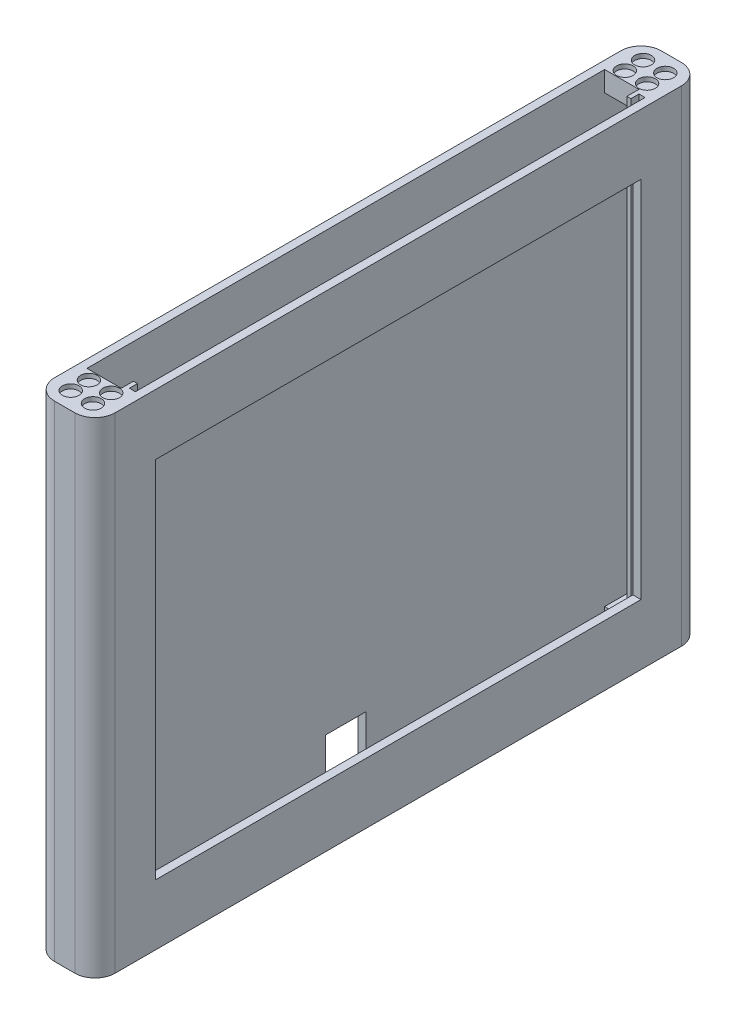
SolidWorks part; units mm, degrees
ref_plane "Front Plane" through (0, 0, 0) normal (0, 0, 1) x (1, 0, 0)
ref_plane "Top Plane" through (0, 0, 0) normal (0, 1, 0) x (1, 0, 0)
ref_plane "Right Plane" through (0, 0, 0) normal (1, 0, 0) x (0, 0, -1)
sketch "Sketch1" plane through (0, 0, 0) normal (1, 0, 0) x (0, 0, -1)
  line L1 (-75, -60) -> (75, -60)
  line L2 (-75, -60) -> (-75, 60)
  line L3 (-75, 60) -> (75, 60)
  line L4 (75, -60) -> (75, 60)
  line L5 (-75, -60) -> (75, 60) construction
  line L6 (-75, 60) -> (75, -60) construction
  point P0 (0, 0)
  dimension "D1" = 150
  dimension "D2" = 120
extrude "Boss-Extrude1" add sketch "Sketch1" against normal blind 15
shell "Shell1" thickness 2
sketch "Sketch2" plane through (0, 0, 0) normal (1, 0, 0) x (0, 0, -1)
  line L1 (-60, -45) -> (60, -45)
  line L2 (-60, -45) -> (-60, 45)
  line L3 (-60, 45) -> (60, 45)
  line L4 (60, -45) -> (60, 45)
  line L5 (-60, -45) -> (60, 45) construction
  line L6 (-60, 45) -> (60, -45) construction
  point P0 (0, 0)
  dimension "D1" = 90
  dimension "D2" = 120
extrude "Cut-Extrude1" cut sketch "Sketch2" against normal up to next
sketch "Sketch3" plane through (0, 0, 0) normal (0, 1, 0) x (1, 0, 0)
  line L0 (-3.5, -63) -> (-3.5, 63) construction
  line L1 (0, 0) -> (50000, 0) construction
  line L2 (-2, 73) -> (-2, -73) construction
  line L3 (-3.5, 63) -> (-2, 63)
  line L4 (-2, 64) -> (-4.5, 64)
  line L5 (-4.5, 64) -> (-4.5, 61)
  line L6 (-4.5, 61) -> (-3.5, 61)
  line L7 (-3.5, 61) -> (-3.5, 63)
  line L8 (-2, 64) -> (-2, 63)
  point P3 (5.2265, 0)
  point P7 (-3.5, 0)
  dimension "D1" = 126
  dimension "D2" = 1.5
  dimension "D3" = 1
  dimension "D4" = 2
  dimension "D5" = 1
extrude "Boss-Extrude2" add sketch "Sketch3" against normal up to surface and the other way up to surface
mirror "Mirror1" about plane through (0, 0, 0) normal (0, 0, 1) of "Boss-Extrude2"
sketch "Sketch4" plane through (0, 60, 0) normal (0, 1, 0) x (1, 0, 0)
  line L1 (-15, 75) -> (-2, 75)
  line L2 (-15, 75) -> (-15, 64)
  line L3 (-15, 64) -> (-2, 64)
  line L4 (-2, 75) -> (-2, 64)
extrude "Boss-Extrude3" add sketch "Sketch4" against normal blind 5
sketch "Sketch5" plane through (0, 60, 0) normal (0, 1, 0) x (1, 0, 0)
  line L0 (-7.5, 73) -> (-7.5, 64) construction
  line L1 (-13, 73) -> (-2, 73) construction
  line L2 (-13, 64) -> (-4.5, 64) construction
  line L3 (-2, 68.5) -> (-13, 68.5) construction
  line L4 (-2, 64) -> (-2, 73) construction
  line L5 (-13, 64) -> (-13, 73) construction
  line L6 (-7.5, 68.5) -> (-13, 73) construction
  line L7 (-7.5, 68.5) -> (-2, 73) construction
  line L8 (-7.5, 68.5) -> (-13, 64) construction
  line L9 (-7.5, 68.5) -> (-2, 64) construction
  circle A0 centre (-10.25, 70.75) radius 2.05
  circle A1 centre (-10.25, 66.25) radius 2.05
  circle A2 centre (-4.75, 70.75) radius 2.05
  circle A3 centre (-4.75, 66.25) radius 2.05
  dimension "magnetD" = 4.1
extrude "Cut-Extrude2" cut sketch "Sketch5" against normal blind 1.1
mirror "Mirror2" about plane through (0, 0, 0) normal (0, 0, 1) of "Boss-Extrude3", "Cut-Extrude2"
sketch "Sketch6" plane through (-15, 0, 0) normal (-1, 0, 0) x (0, 0, 1)
  line L0 (0, -58) -> (0, 49942) construction
  line L1 (73, -58) -> (-73, -58) construction
  line L8 (-5, -48) -> (5, -48)
  line L9 (-5, -48) -> (-5, -58)
  line L10 (-5, -58) -> (5, -58)
  line L11 (5, -48) -> (5, -58)
  line L12 (-5, -48) -> (5, -58) construction
  line L13 (-5, -58) -> (5, -48) construction
  point P4 (0, -58)
  point P5 (0, -53)
  dimension "D1" = 10
  dimension "D2" = 10
extrude "Cut-Extrude3" cut sketch "Sketch6" against normal up to surface (2 mm away) up to face at (-13, 28, 0)
mirror "Mirror3" about plane through (0, 0, 0) normal (0, 1, 0) of "Mirror2", "Boss-Extrude3", "Cut-Extrude2"
fillet "Fillet1" radius 5 4 edges at (-15, 0, -75) (0, 0, -75) (-15, 0, 75) (0, 0, 75)
